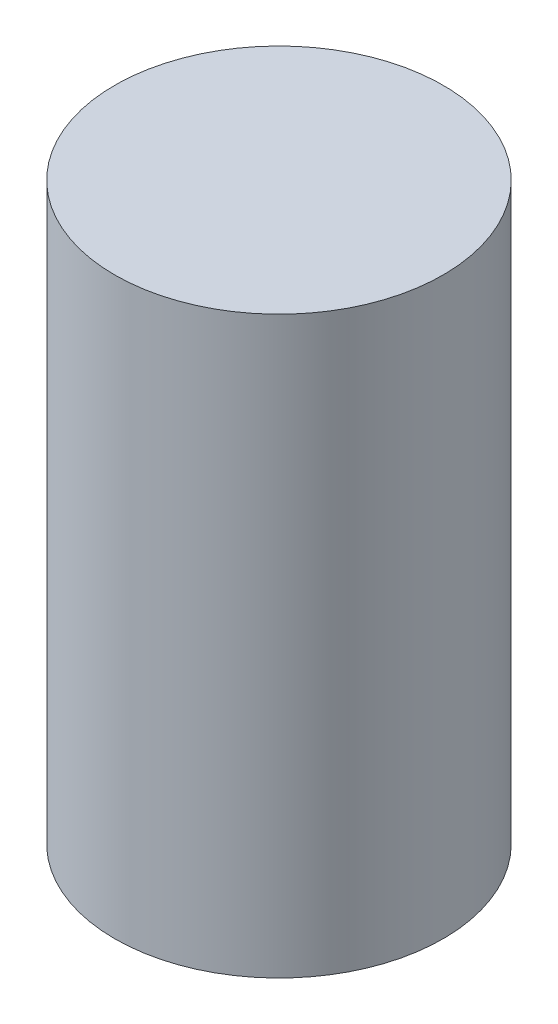
SolidWorks part; units mm, degrees
ref_plane "Plan de face" through (0, 0, 0) normal (0, 0, 1) x (1, 0, 0)
ref_plane "Plan de dessus" through (0, 0, 0) normal (0, 1, 0) x (1, 0, 0)
ref_plane "Plan de droite" through (0, 0, 0) normal (1, 0, 0) x (0, 0, -1)
sketch "Esquisse2" plane through (0, 0, 0) normal (0, 1, 0) x (1, 0, 0)
  circle A0 centre (0, 0) radius 10
extrude "Boss.-Extru.2" add sketch "Esquisse2" along normal blind 35
sketch "Esquisse4" plane through (0, 0, 0) normal (0, -1, 0) x (1, 0, 0)
  circle A0 centre (0, 0) radius 6
sketch "Esquisse5" plane through (0, 35, 0) normal (0, 1, 0) x (1, 0, 0)
  line L0 (-10, 0) -> (10, 0) construction
  line L1 (5, -8.6603) -> (5, 8.6603)
  line L2 (-5, -8.6603) -> (-5, 8.6603)
  circle A1 centre (0, 0) radius 10 construction
  point P7 (0, 0)
  point P10 (0, 0)
  point P11 (5, 0)
  point P15 (-5, 0)
  dimension "D1" = 5
  dimension "D2" = 5
